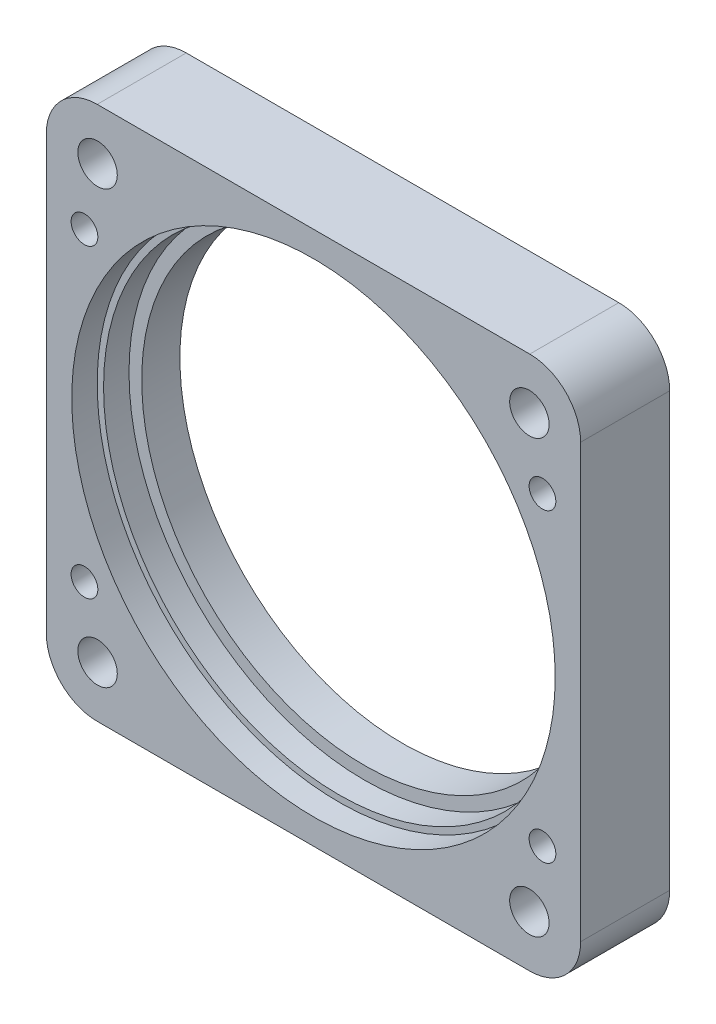
SolidWorks part; units mm, degrees
ref_plane "前视基准面" through (0, 0, 0) normal (0, 0, 1) x (1, 0, 0)
ref_plane "上视基准面" through (0, 0, 0) normal (0, 1, 0) x (1, 0, 0)
ref_plane "右视基准面" through (0, 0, 0) normal (1, 0, 0) x (0, 0, -1)
sketch "草图1" plane through (0, 0, 0) normal (0, 0, 1) x (1, 0, 0)
  line L1 (-21, 21) -> (21, 21)
  line L2 (-21, 21) -> (-21, -21)
  line L3 (-21, -21) -> (21, -21)
  line L4 (21, 21) -> (21, -21)
  line L5 (0, -21) -> (0, 21) construction
  line L6 (-21, 0) -> (21, 0) construction
  point P0 (0, 0)
  dimension "D1" = 42
  dimension "D2" = 42
extrude "凸台-拉伸1" add sketch "草图1" along normal blind 7
sketch "草图2" plane through (0, 0, 7) normal (0, 0, 1) x (1, 0, 0)
  circle A0 centre (0, 0) radius 17.5
  dimension "D1" = 35
extrude "切除-拉伸1" cut sketch "草图2" against normal through all
sketch "草图3" plane through (0, 0, 7) normal (0, 0, 1) x (1, 0, 0)
  circle A0 centre (0, 0) radius 18.5
  dimension "D1" = 37
extrude "切除-拉伸2" cut sketch "草图3" against normal offset from surface (4 mm away) 3 up to face at (17.5, 0, 0)
sketch "草图4" plane through (0, 0, 7) normal (0, 0, 1) x (1, 0, 0)
  circle A0 centre (0, 0) radius 19
  dimension "D1" = 38
extrude "切除-拉伸3" cut sketch "草图4" against normal offset from surface (2 mm away) 2 contours A0 up to face at (18.5, 0, 3)
fillet "圆角1" radius 4 4 edges at (-21, -21, 3.5) (21, -21, 3.5) (21, 21, 3.5) (-21, 21, 3.5)
sketch "草图5" plane through (0, 0, 7) normal (0, 0, 1) x (1, 0, 0)
  circle A0 centre (-16.9706, 16.9706) radius 1.55
  circle A3 centre (16.9706, 16.9706) radius 1.55
  circle A4 centre (16.9706, -16.9706) radius 1.55
  circle A5 centre (-16.9706, -16.9706) radius 1.55
  point P12 (0, 0)
  dimension "D1" = 3.1
  dimension "D2" = 24
  dimension "D4" = 4
sketch "草图6" plane through (0, 0, 7) normal (0, 0, 1) x (1, 0, 0)
  line L0 (-21, 17) -> (-21, -17) construction
  line L2 (-21, -9) -> (-21, -13)
  line L3 (-21, -13) -> (-17, -13)
  line L5 (-21, -9) -> (-17, -13)
  line L6 (-17, -21) -> (17, -21) construction
  line L7 (-9, 21) -> (-13, 17)
  line L8 (-13, 21) -> (-13, 17)
  line L9 (-9, 21) -> (-13, 21)
  line L10 (21, 9) -> (17, 13)
  line L11 (21, 13) -> (17, 13)
  line L12 (21, 9) -> (21, 13)
  line L13 (9, -21) -> (13, -17)
  line L14 (13, -21) -> (13, -17)
  line L15 (9, -21) -> (13, -21)
  point P19 (0, 0)
  dimension "D1" = 4
  dimension "D2" = 4
  dimension "D3" = 8
  dimension "D4" = 4
extrude "凸台-拉伸2" [suppressed] add sketch "草图6" along normal blind 3
pattern_circular "阵列(圆周)1" [suppressed] count 4 over 360
extrude "切除-拉伸4" cut sketch "草图5" against normal through all
sketch "草图7" plane through (0, 0, 0) normal (0, 0, -1) x (-1, 0, 0)
  line L0 (-21, -17) -> (-21, 17) construction
  line L1 (-17, 21) -> (17, 21) construction
  line L2 (-28.4314, 0) -> (27.643, 0) construction
  line L4 (0, 29.0062) -> (0, -29.8069) construction
  circle A0 centre (-18, 12) radius 1.05
  circle A4 centre (18, 12) radius 1.05
  circle A5 centre (18, -12) radius 1.05
  circle A6 centre (-18, -12) radius 1.05
  dimension "D1" = 2.1
  dimension "D2" = 3
  dimension "D3" = 9
extrude "切除-拉伸5" cut sketch "草图7" against normal through all
sketch "草图8" plane through (0, 0, 0) normal (0, 0, -1) x (-1, 0, 0)
  line L2 (-28.4314, 0) -> (27.643, 0) construction
  line L3 (-28.4314, 0) -> (27.643, 0) construction
  line L4 (0, 29.0062) -> (0, -29.8069) construction
  line L5 (0, 29.0062) -> (0, -29.8069) construction
  circle A0 centre (-18, 12) radius 2
  circle A1 centre (18, 12) radius 2
  circle A2 centre (18, -12) radius 2
  circle A3 centre (-18, -12) radius 2
  dimension "D1" = 4
extrude "切除-拉伸6" cut sketch "草图8" against normal blind 3
